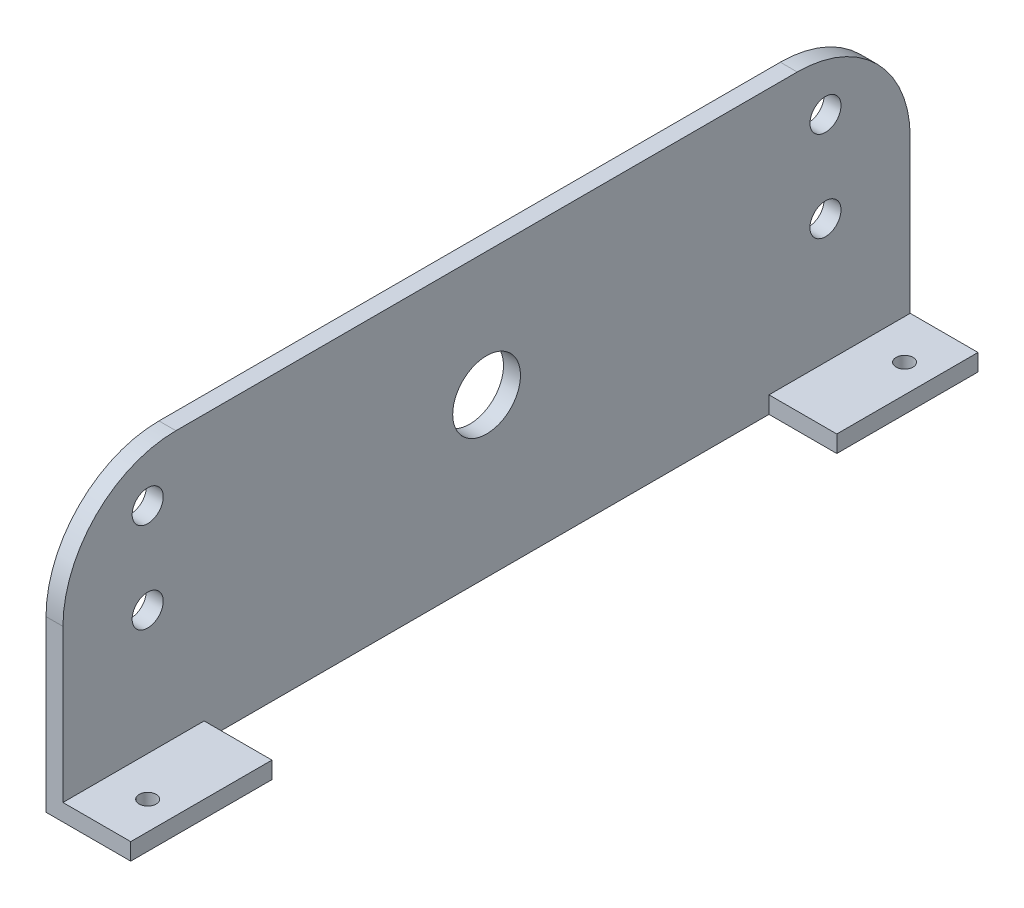
SolidWorks part; units mm, degrees
ref_plane "正面" through (0, 0, 0) normal (0, 0, 1) x (1, 0, 0)
ref_plane "平面" through (0, 0, 0) normal (0, 1, 0) x (1, 0, 0)
ref_plane "右側面" through (0, 0, 0) normal (1, 0, 0) x (0, 0, -1)
ref_plane "平面1" through (0, 0, 0) normal (-1, 0, 0) x (0, -1, 0)
sketch "ｽｹｯﾁ1" plane through (0, 0, 0) normal (-1, 0, 0) x (0, -1, 0)
  line L0 (-50, 75) -> (-50, -75)
  line L1 (-50, -75) -> (0, -75)
  line L2 (0, -75) -> (0, 75)
  line L3 (0, 75) -> (-50, 75)
extrude "ﾎﾞｽ - 押し出し1" add sketch "ｽｹｯﾁ1" against normal blind 3
sketch "ｽｹｯﾁ2" plane through (3, 0, 0) normal (1, 0, 0) x (0, 0, -1)
  line L0 (-75, 0) -> (-75, 3)
  line L1 (-75, 3) -> (-50, 3)
  line L2 (-50, 3) -> (-50, 0)
  line L3 (-50, 0) -> (-75, 0)
extrude "ﾎﾞｽ - 押し出し2" add sketch "ｽｹｯﾁ2" along normal blind 12
sketch "ｽｹｯﾁ3" plane through (3, 0, 0) normal (1, 0, 0) x (0, 0, -1)
  line L0 (75, 3) -> (75, 0)
  line L1 (75, 0) -> (50, 0)
  line L2 (50, 0) -> (50, 3)
  line L3 (50, 3) -> (75, 3)
extrude "ﾎﾞｽ - 押し出し3" add sketch "ｽｹｯﾁ3" along normal blind 12
hole_wizard "Ø3.0 (3) 直径の穴1" positions "ｽｹｯﾁ5" profile "ｽｹｯﾁ4" hole size "Ø3.0" standard "Ansi Metric"
sketch "ｽｹｯﾁ5" plane through (0, 0, 0) normal (0, -1, 0) x (-1, 0, 0)
  point P0 (-10, -67)
  point P1 (-10, 67)
sketch "ｽｹｯﾁ4" plane through (10, 0, 67) normal (1, 0, 0) x (0, 0, -1)
  line L0 (0, 0) -> (0, 50)
  line L1 (0, 50) -> (1.5, 50)
  line L2 (1.5, 50) -> (1.5, 0)
  line L5 (1.5, 0) -> (0, 0)
  line L11 (0, -6.35) -> (0, 107.95) construction
  dimension "通し穴の直径" = 3
  dimension "通し穴の深さ" = 50
hole_wizard "Ø5.5 (5.5) 直径の穴1" positions "ｽｹｯﾁ7" profile "ｽｹｯﾁ6" hole size "Ø5.5" standard "Ansi Metric"
sketch "ｽｹｯﾁ7" plane through (3, 0, 0) normal (1, 0, 0) x (0, 0, -1)
  point P0 (60, 41)
  point P1 (-60, 41)
  point P2 (-60, 25)
  point P3 (60, 25)
sketch "ｽｹｯﾁ6" plane through (3, 41, -60) normal (0, 1, 0) x (0, 0, -1)
  line L0 (0, 0) -> (0, 3)
  line L1 (0, 3) -> (2.75, 3)
  line L2 (2.75, 3) -> (2.75, 0)
  line L5 (2.75, 0) -> (0, 0)
  line L11 (0, -6.35) -> (0, 107.95) construction
  dimension "通し穴の直径" = 5.5
  dimension "通し穴の深さ" = 3
hole_wizard "Ø12.0 (12) 直径の穴1" positions "ｽｹｯﾁ9" profile "ｽｹｯﾁ8" hole size "Ø12.0" standard "Ansi Metric"
sketch "ｽｹｯﾁ9" plane through (0, 0, 0) normal (-1, 0, 0) x (0, 0, 1)
  point P0 (0, 28)
sketch "ｽｹｯﾁ8" plane through (0, 28, 0) normal (0, 1, 0) x (0, 0, 1)
  line L0 (0, 0) -> (0, 15)
  line L1 (0, 15) -> (6, 15)
  line L2 (6, 15) -> (6, 0)
  line L5 (6, 0) -> (0, 0)
  line L11 (0, -6.35) -> (0, 107.95) construction
  dimension "通し穴の直径" = 12
  dimension "通し穴の深さ" = 15
fillet "ﾌｨﾚｯﾄ1" radius 20 2 edges at (1.5, 50, 75) (1.5, 50, -75)
